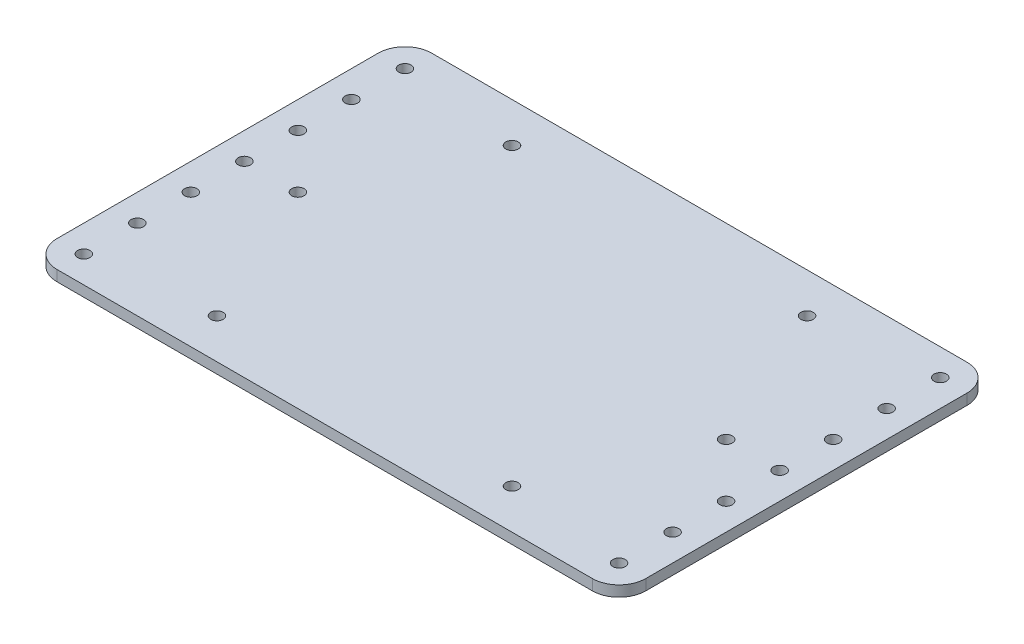
SolidWorks part; units mm, degrees
ref_plane "Front Plane" through (0, 0, 0) normal (0, 0, 1) x (1, 0, 0)
ref_plane "Top Plane" through (0, 0, 0) normal (0, 1, 0) x (1, 0, 0)
ref_plane "Right Plane" through (0, 0, 0) normal (1, 0, 0) x (0, 0, -1)
sketch "Sketch1" plane through (0, 0, 0) normal (0, 1, 0) x (1, 0, 0)
  line L0 (34.85, -5.7838) -> (34.85, -13.1162) construction
  line L1 (0, 0) -> (139.7, 0)
  line L2 (0, 0) -> (0, -88.9)
  line L3 (0, -88.9) -> (139.7, -88.9)
  line L4 (139.7, 0) -> (139.7, -88.9)
  line L5 (31.675, -9.45) -> (38.025, -9.45) construction
  line L6 (103.0169, -12.625) -> (101.1838, -9.45) construction
  line L7 (106.6831, -12.625) -> (103.0169, -12.625) construction
  line L8 (69.85, 0) -> (69.85, -88.9) construction
  line L9 (0, -44.45) -> (139.7, -44.45) construction
  line L10 (108.5162, -9.45) -> (106.6831, -12.625) construction
  line L11 (106.6831, -6.275) -> (108.5162, -9.45) construction
  line L12 (103.0169, -6.275) -> (106.6831, -6.275) construction
  line L13 (101.1838, -9.45) -> (103.0169, -6.275) construction
  line L14 (101.675, -77.6169) -> (104.85, -75.7838) construction
  line L15 (101.675, -81.2831) -> (101.675, -77.6169) construction
  line L16 (34.85, -5.7838) -> (38.025, -7.6169) construction
  line L17 (44.85, -19.45) -> (94.85, -19.45) construction
  line L18 (44.85, -19.45) -> (44.85, -69.45) construction
  line L19 (44.85, -69.45) -> (94.85, -69.45) construction
  line L20 (94.85, -19.45) -> (94.85, -69.45) construction
  line L21 (44.85, -19.45) -> (94.85, -69.45) construction
  line L22 (44.85, -69.45) -> (94.85, -19.45) construction
  line L23 (38.025, -7.6169) -> (38.025, -11.2831) construction
  line L24 (38.025, -11.2831) -> (34.85, -13.1162) construction
  line L25 (34.85, -13.1162) -> (31.675, -11.2831) construction
  line L26 (31.675, -11.2831) -> (31.675, -7.6169) construction
  line L27 (31.675, -7.6169) -> (34.85, -5.7838) construction
  line L28 (104.85, -83.1162) -> (101.675, -81.2831) construction
  line L29 (108.025, -81.2831) -> (104.85, -83.1162) construction
  line L30 (108.025, -77.6169) -> (108.025, -81.2831) construction
  line L31 (104.85, -75.7838) -> (108.025, -77.6169) construction
  line L32 (36.6831, -76.275) -> (38.5162, -79.45) construction
  line L33 (33.0169, -76.275) -> (36.6831, -76.275) construction
  line L34 (31.1838, -79.45) -> (33.0169, -76.275) construction
  line L35 (33.0169, -82.625) -> (31.1838, -79.45) construction
  line L36 (36.6831, -82.625) -> (33.0169, -82.625) construction
  line L37 (38.5162, -79.45) -> (36.6831, -82.625) construction
  line L38 (19.05, -44.45) -> (69.85, -44.45) construction
  line L39 (69.85, -44.45) -> (120.65, -44.45) construction
  circle A12 centre (34.85, -9.45) radius 1.4732
  circle A13 centre (6.35, -6.35) radius 1.4732
  circle A16 centre (6.35, -19.05) radius 1.4732
  circle A17 centre (6.35, -31.75) radius 1.4732
  circle A18 centre (6.35, -44.45) radius 1.4732
  circle A19 centre (6.35, -57.15) radius 1.4732
  circle A20 centre (6.35, -69.85) radius 1.4732
  circle A21 centre (6.35, -82.55) radius 1.4732
  circle A22 centre (104.85, -9.45) radius 1.4732
  circle A23 centre (104.85, -79.45) radius 1.4732
  circle A24 centre (34.85, -79.45) radius 1.4732
  circle A25 centre (133.35, -82.55) radius 1.4732
  circle A26 centre (133.35, -69.85) radius 1.4732
  circle A27 centre (133.35, -57.15) radius 1.4732
  circle A28 centre (133.35, -44.45) radius 1.4732
  circle A29 centre (133.35, -31.75) radius 1.4732
  circle A30 centre (133.35, -19.05) radius 1.4732
  circle A31 centre (133.35, -6.35) radius 1.4732
  circle A32 centre (19.05, -44.45) radius 1.4732
  circle A33 centre (120.65, -44.45) radius 1.4732
  point P18 (69.85, -44.45)
  point P44 (69.85, -44.45)
  point P45 (34.85, -9.45)
  point P67 (69.85, -44.45)
  point P83 (-11.9793, -44.45)
  point P85 (-37.1413, -44.45)
  dimension "D5" = 2.9464
  dimension "D4" = 139.7
  dimension "D7" = 50
  dimension "D8" = 6.35
  dimension "D9" = 6.35
  dimension "D3" = 88.9
  dimension "D1" = 35
  dimension "D2" = 35
  dimension "D6" = 63.5
  dimension "D10" = 38.1
  dimension "D12" = 12.7
  dimension "D14" = 70
  dimension "D15" = 50.8
  dimension "D11" = 7
  dimension "D13" = 4
extrude "Boss-Extrude1" add sketch "Sketch1" along normal blind 2.54
fillet "Fillet1" radius 6.35 4 edges at (0, 1.27, 0) (139.7, 1.27, 0) (139.7, 1.27, 88.9) (0, 1.27, 88.9)
equation "\"D2@Sketch1\"=\"D1@Sketch1\""
